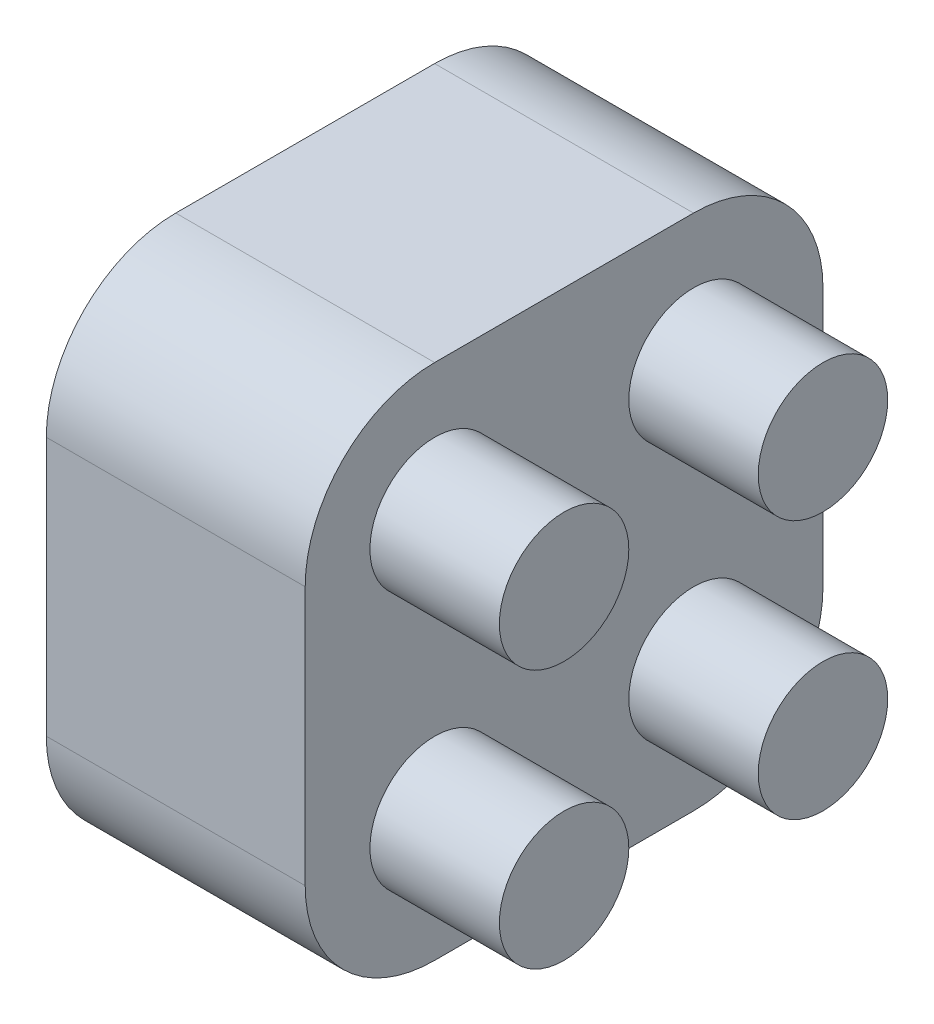
SolidWorks part; units mm, degrees
ref_plane "Front Plane" through (0, 0, 0) normal (0, 0, 1) x (1, 0, 0)
ref_plane "Top Plane" through (0, 0, 0) normal (0, 1, 0) x (1, 0, 0)
ref_plane "Right Plane" through (0, 0, 0) normal (1, 0, 0) x (0, 0, -1)
sketch "Sketch5" plane through (0, 0, 0) normal (1, 0, 0) x (0, 0, -1)
  line L1 (0, 0) -> (20, 0)
  line L2 (0, 0) -> (0, 20)
  line L3 (0, 20) -> (20, 20)
  line L4 (20, 0) -> (20, 20)
  dimension "D1" = 20
extrude "Boss-Extrude1" add sketch "Sketch5" along normal blind 10
sketch "Sketch6" plane through (10, 0, 0) normal (1, 0, 0) x (0, 0, -1)
  line L0 (0, 20) -> (0, 0) construction
  line L1 (20, 20) -> (0, 20) construction
  circle A0 centre (5, 15) radius 2.5
  circle A1 centre (15, 15) radius 2.5
  circle A2 centre (15, 5) radius 2.5
  circle A3 centre (5, 5) radius 2.5
  dimension "D1" = 5
  dimension "D2" = 5
  dimension "D3" = 5
  dimension "D4" = 2
  dimension "D5" = 2
extrude "Boss-Extrude2" add sketch "Sketch6" along normal blind 5
fillet "Fillet1" radius 5 4 edges at (5, 0, -20) (5, 0, 0) (5, 20, 0) (5, 20, -20)
shell "Shell2" thickness 2
